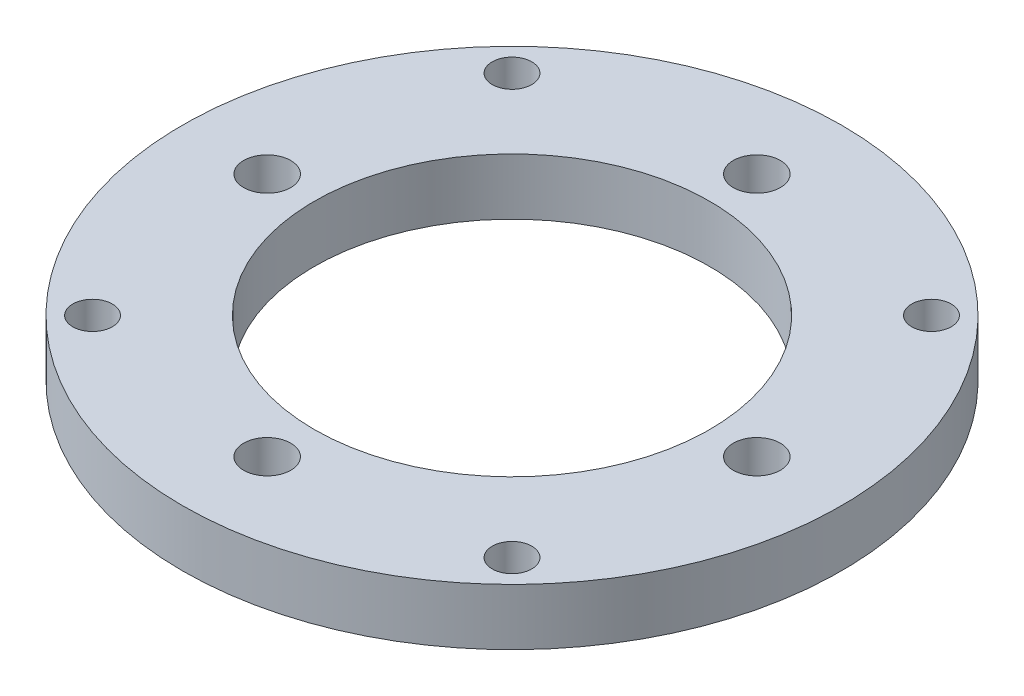
SolidWorks part; units mm, degrees
ref_plane "Спереди" through (0, 0, 0) normal (0, 0, 1) x (1, 0, 0)
ref_plane "Сверху" through (0, 0, 0) normal (0, 1, 0) x (1, 0, 0)
ref_plane "Справа" through (0, 0, 0) normal (1, 0, 0) x (0, 0, -1)
sketch "Эскиз1" plane through (0, 0, 0) normal (0, 1, 0) x (1, 0, 0)
  circle A0 centre (0, 0) radius 35
  dimension "D1" = 70
extrude "Бобышка-Вытянуть1" add sketch "Эскиз1" along normal blind 6
sketch "Эскиз2" plane through (0, 6, 0) normal (0, 1, 0) x (1, 0, 0)
  line L0 (0, 26) -> (0, -26) construction
  line L1 (0, 0) -> (22.2739, 22.2739) construction
  line L2 (0, 0) -> (-22.2739, -22.2739) construction
  line L3 (0, 0) -> (-22.2739, 22.2739) construction
  line L4 (0, 0) -> (22.2739, -22.2739) construction
  circle A0 centre (0, 0) radius 21
  circle A1 centre (0, 0) radius 26 construction
  circle A2 centre (0, 26) radius 2.5
  circle A3 centre (0, -26) radius 2.5
  circle A4 centre (26, 0) radius 2.5
  circle A5 centre (-26, 0) radius 2.5
  circle A6 centre (0, 0) radius 31.5 construction
  circle A7 centre (-22.2739, 22.2739) radius 2.1
  circle A8 centre (-22.2739, -22.2739) radius 2.1
  circle A9 centre (22.2739, -22.2739) radius 2.1
  circle A10 centre (22.2739, 22.2739) radius 2.1
  dimension "D1" = 42
  dimension "D2" = 52
  dimension "D3" = 5
  dimension "D4" = 5
  dimension "D5" = 5
  dimension "D6" = 5
  dimension "D7" = 63
  dimension "D9" = 4.2
  dimension "D10" = 4.2
  dimension "D11" = 4.2
  dimension "D12" = 4.2
  dimension "D8" = 45
extrude "Вырез-Вытянуть1" cut sketch "Эскиз2" against normal blind 10
chamfer "Фаска1" distance 2 angle 45 4 edges at (-26, 0, 2.5) (0, 0, -23.5) (26, 0, 2.5) (0, 0, 28.5)
